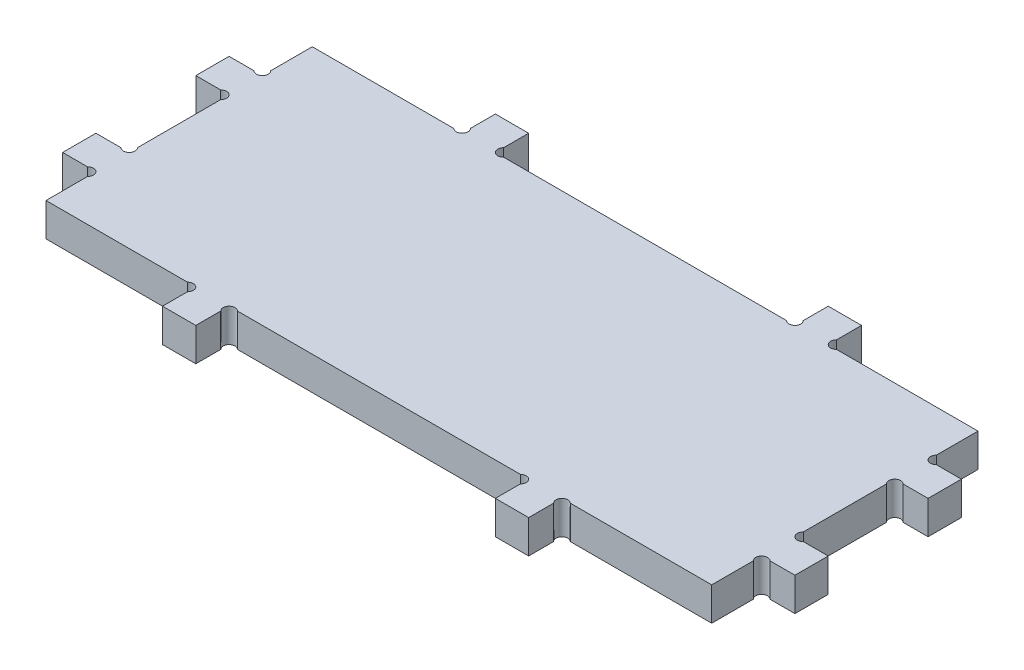
SolidWorks part; units mm, degrees
material "6061 Alloy"
ref_plane "Front" through (0, 0, 0) normal (0, 0, 1) x (1, 0, 0)
ref_plane "Top" through (0, 0, 0) normal (0, 1, 0) x (1, 0, 0)
ref_plane "Right" through (0, 0, 0) normal (1, 0, 0) x (0, 0, -1)
sketch "Sketch2" plane through (0, 0, 0) normal (0, 1, 0) x (1, 0, 0)
  line L1 (-127, -50.8) -> (127, -50.8)
  line L2 (-127, -50.8) -> (-127, 50.8)
  line L3 (-127, 50.8) -> (127, 50.8)
  line L4 (127, -50.8) -> (127, 50.8)
  line L5 (-127, -50.8) -> (127, 50.8) construction
  line L6 (-127, 50.8) -> (127, -50.8) construction
  point P0 (0, 0)
  dimension "D1" = 254
  dimension "D2" = 101.6
extrude "Rectangle Extrusion" add sketch "Sketch2" along normal blind 12.7
sketch "Sketch4" plane through (0, 0, 50.8) normal (0, 0, 1) x (1, 0, 0)
  line L0 (-127, 12.7) -> (-63.5, 12.7) construction
  line L1 (-127, 12.7) -> (127, 12.7) construction
  line L2 (-63.5, 12.7) -> (-63.5, 6.35) construction
  line L3 (-127, 0) -> (127, 0) construction
  line L4 (-57.15, 12.7) -> (-69.85, 12.7)
  line L5 (-57.15, 12.7) -> (-57.15, 0)
  line L6 (-57.15, 0) -> (-69.85, 0)
  line L7 (-69.85, 12.7) -> (-69.85, 0)
  line L8 (-57.15, 12.7) -> (-69.85, 0) construction
  line L9 (-57.15, 0) -> (-69.85, 12.7) construction
  line L10 (0, 12.7) -> (0, 0) construction
  line L11 (57.15, 0) -> (69.85, 0)
  line L12 (69.85, 12.7) -> (69.85, 0)
  line L13 (57.15, 12.7) -> (69.85, 12.7)
  line L14 (57.15, 12.7) -> (57.15, 0)
  dimension "D1" = 63.5
  dimension "D2" = 6.35
  dimension "D3" = 12.7
extrude "Front Face Tabs" add sketch "Sketch4" along normal blind 12.7
mirror "Mirror Rear Face Tabs" about plane through (0, 0, 0) normal (0, 0, 1) of "Front Face Tabs"
sketch "Sketch6" plane through (0, 12.7, 0) normal (0, 1, 0) x (1, 0, 0)
  line L0 (-69.85, 50.8) -> (-127, 50.8) construction
  line L1 (-69.85, 63.5) -> (-69.85, 50.8) construction
  line L2 (-63.5, 63.5) -> (-63.5, 50.1421) construction
  line L3 (-57.15, 63.5) -> (-69.85, 63.5) construction
  line L4 (0, -6.985) -> (0, 6.985) construction
  line L5 (-6.985, 0) -> (6.985, 0) construction
  circle A0 centre (-71.4375, 52.3875) radius 2.2454
  circle A1 centre (-55.5625, 52.3875) radius 2.2454
  circle A2 centre (55.5625, 52.3875) radius 2.2454
  circle A3 centre (71.4375, 52.3875) radius 2.2454
  circle A4 centre (71.4375, -52.3875) radius 2.2454
  circle A5 centre (55.5625, -52.3875) radius 2.2454
  circle A6 centre (-55.5625, -52.3875) radius 2.2454
  circle A7 centre (-71.4375, -52.3875) radius 2.2454
  dimension "D1" = 1.5875
  dimension "D3" = 4.4907
  dimension "D2" = 1.5875
extrude "Tab Curve Front Back" cut sketch "Sketch6" against normal up to surface (12.7 mm away) up to face at (0, 0, 0)
sketch "Sketch7" plane through (127, 0, 0) normal (1, 0, 0) x (0, 0, -1)
  line L0 (-50.8, 12.7) -> (-25.4, 12.7) construction
  line L1 (-50.8, 12.7) -> (50.8, 12.7) construction
  line L2 (-25.4, 12.7) -> (-25.4, 0) construction
  line L3 (69.85, 0) -> (-69.85, 0) construction
  line L4 (0, 6.985) -> (0, -6.985) construction
  line L5 (-31.75, 12.7) -> (-19.05, 12.7)
  line L6 (-31.75, 12.7) -> (-31.75, 0)
  line L7 (-31.75, 0) -> (-19.05, 0)
  line L8 (-19.05, 12.7) -> (-19.05, 0)
  line L9 (-31.75, 12.7) -> (-19.05, 0) construction
  line L10 (-31.75, 0) -> (-19.05, 12.7) construction
  line L11 (31.75, 0) -> (19.05, 0)
  line L12 (19.05, 12.7) -> (19.05, 0)
  line L13 (31.75, 12.7) -> (19.05, 12.7)
  line L14 (31.75, 12.7) -> (31.75, 0)
  point P5 (-25.4, 6.35)
  dimension "D1" = 25.4
  dimension "D2" = 12.7
extrude "Right Face Tabs" add sketch "Sketch7" along normal blind 12.7
mirror "Mirror Left Face Tabs" about plane through (0, 0, 0) normal (1, 0, 0) of "Right Face Tabs"
sketch "Sketch8" plane through (0, 12.7, 0) normal (0, 1, 0) x (1, 0, 0)
  line L0 (139.7, 31.75) -> (127, 31.75) construction
  line L1 (127, 31.75) -> (127, 50.8) construction
  line L2 (139.7, 25.4) -> (126.2032, 25.4) construction
  line L3 (139.7, 31.75) -> (139.7, 19.05) construction
  line L4 (-6.985, 0) -> (6.985, 0) construction
  line L5 (0, -6.985) -> (0, 6.985) construction
  circle A0 centre (128.5875, 33.3375) radius 2.2454
  circle A1 centre (128.5875, 17.4625) radius 2.2454
  circle A2 centre (128.5875, -17.4625) radius 2.2454
  circle A3 centre (128.5875, -33.3375) radius 2.2454
  circle A4 centre (-128.5875, -33.3375) radius 2.2454
  circle A5 centre (-128.5875, -17.4625) radius 2.2454
  circle A6 centre (-128.5875, 17.4625) radius 2.2454
  circle A7 centre (-128.5875, 33.3375) radius 2.2454
  dimension "D3" = 4.4907
  dimension "D1" = 1.5875
  dimension "D2" = 1.5875
extrude "Tab Curve Left Right" cut sketch "Sketch8" against normal up to surface (12.7 mm away) up to face at (0, 0, 0)
